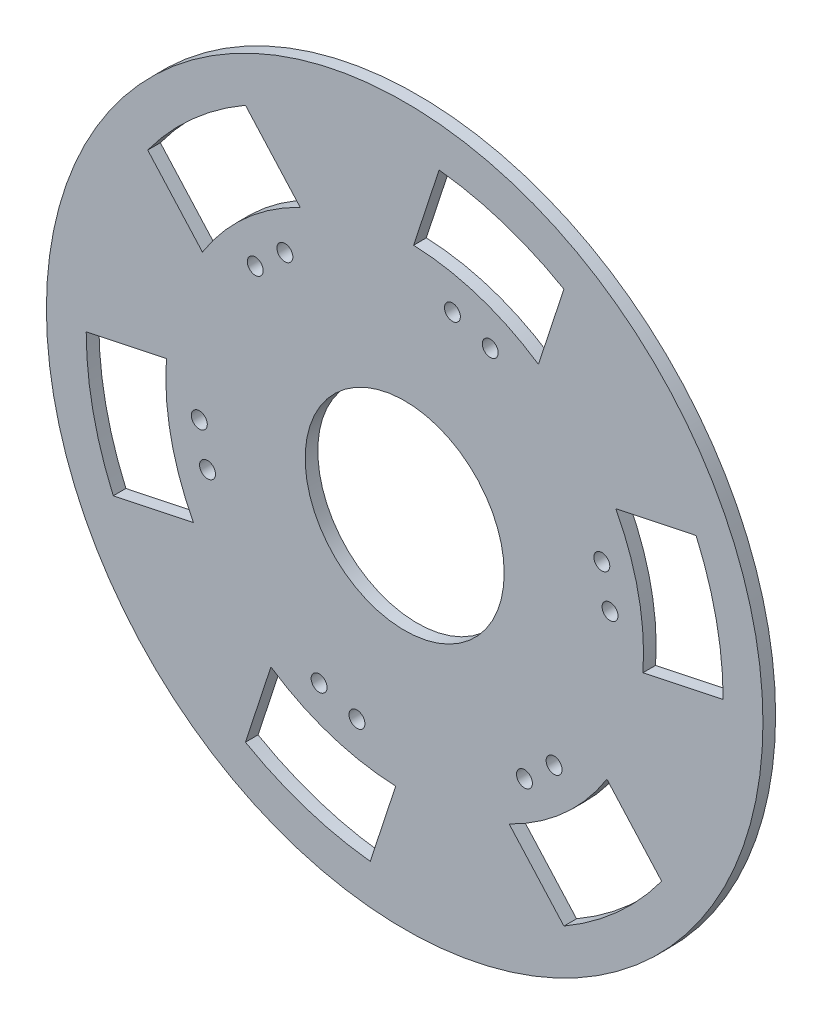
SolidWorks part; units mm, degrees
ref_plane "Front Plane" through (0, 0, 0) normal (0, 0, 1) x (1, 0, 0)
ref_plane "Top Plane" through (0, 0, 0) normal (0, 1, 0) x (1, 0, 0)
ref_plane "Right Plane" through (0, 0, 0) normal (1, 0, 0) x (0, 0, -1)
sketch "Sketch1" plane through (0, 0, 0) normal (0, 0, 1) x (1, 0, 0)
  circle A0 centre (0, 0) radius 90
  circle A1 centre (0, 0) radius 25
  dimension "D1" = 180
  dimension "D2" = 50
extrude "Boss-Extrude1" add sketch "Sketch1" along normal blind 3.175 contours A0 A1
sketch "Sketch2" plane through (0, 0, 0) normal (0, 0, -1) x (-1, 0, 0)
  circle A0 centre (-49.5233, 14.7488) radius 2
  circle A1 centre (-51.5847, 4.9636) radius 2
  circle A2 centre (-37.5345, -35.514) radius 2
  circle A3 centre (-30.091, -42.1919) radius 2
  circle A4 centre (11.9888, -50.2628) radius 2
  circle A5 centre (21.4938, -47.1555) radius 2
  circle A6 centre (49.5233, -14.7488) radius 2
  circle A7 centre (51.5847, -4.9636) radius 2
  circle A8 centre (37.5345, 35.514) radius 2
  circle A9 centre (30.091, 42.1919) radius 2
  circle A10 centre (-21.4938, 47.1555) radius 2
  circle A11 centre (-11.9888, 50.2628) radius 2
extrude "Cut-Extrude1" cut sketch "Sketch2" against normal through all
sketch "Sketch3" plane through (0, 0, 3.175) normal (0, 0, 1) x (1, 0, 0)
  line L0 (-49.5233, -14.7488) -> (-51.5847, -4.9636) construction
  line L1 (-21.4938, -47.1555) -> (-11.9888, -50.2628) construction
  line L2 (30.091, -42.1919) -> (37.5345, -35.514) construction
  line L3 (49.5233, 14.7488) -> (51.5847, 4.9636) construction
  line L4 (21.4938, 47.1555) -> (11.9888, 50.2628) construction
  line L5 (-30.091, 42.1919) -> (-37.5345, 35.514) construction
  line L6 (-88.0669, -18.553) -> (88.0669, 18.553) construction
  line L7 (-27.9661, -85.5447) -> (27.9661, 85.5447) construction
  line L8 (60.1009, -66.9917) -> (-60.1009, 66.9917) construction
  line L9 (-80, 0) -> (-62.1109, 3.7687)
  line L10 (-80, 0) -> (-73.2007, -32.2747)
  line L11 (-62.1109, 3.7687) -> (-55.3116, -28.506)
  line L12 (-73.2007, -32.2747) -> (-55.3116, -28.506)
  line L13 (-64.2562, -30.3904) -> (-71.0555, 1.8843) construction
  line L14 (-73.2007, -32.2747) -> (-53.0503, -28.0296)
  line L15 (-80, 0) -> (-59.8496, 4.2451)
  line L16 (-40, 69.282) -> (-27.7917, 55.674)
  line L17 (-40, 69.282) -> (-64.5511, 47.2563)
  line L18 (-64.5511, 47.2563) -> (-52.3428, 33.6483)
  line L19 (-27.7917, 55.674) -> (-52.3428, 33.6483)
  line L20 (-40, 69.282) -> (-26.2485, 53.9538)
  line L21 (-64.5511, 47.2563) -> (-50.7996, 31.9281)
  line L22 (40, 69.282) -> (34.3192, 51.9053)
  line L23 (40, 69.282) -> (8.6496, 79.531)
  line L24 (8.6496, 79.531) -> (2.9689, 62.1543)
  line L25 (34.3192, 51.9053) -> (2.9689, 62.1543)
  line L26 (40, 69.282) -> (33.6012, 49.7088)
  line L27 (8.6496, 79.531) -> (2.2508, 59.9578)
  line L28 (80, 0) -> (62.1109, -3.7687)
  line L29 (80, 0) -> (73.2007, 32.2747)
  line L30 (73.2007, 32.2747) -> (55.3116, 28.506)
  line L31 (62.1109, -3.7687) -> (55.3116, 28.506)
  line L32 (80, 0) -> (59.8496, -4.2451)
  line L33 (73.2007, 32.2747) -> (53.0503, 28.0296)
  line L34 (40, -69.282) -> (27.7917, -55.674)
  line L35 (40, -69.282) -> (64.5511, -47.2563)
  line L36 (64.5511, -47.2563) -> (52.3428, -33.6483)
  line L37 (27.7917, -55.674) -> (52.3428, -33.6483)
  line L38 (40, -69.282) -> (26.2485, -53.9538)
  line L39 (64.5511, -47.2563) -> (50.7996, -31.9281)
  line L40 (-40, -69.282) -> (-34.3192, -51.9053)
  line L41 (-40, -69.282) -> (-8.6496, -79.531)
  line L42 (-8.6496, -79.531) -> (-2.9689, -62.1543)
  line L43 (-34.3192, -51.9053) -> (-2.9689, -62.1543)
  line L44 (-40, -69.282) -> (-33.6012, -49.7088)
  line L45 (-8.6496, -79.531) -> (-2.2508, -59.9578)
  circle A0 centre (0, 0) radius 60
  circle A1 centre (0, 0) radius 80
  circle A2 centre (0, 0) radius 90 construction
  point P19 (0, 0)
  point P38 (0, 0)
  point P45 (0, 0)
  point P46 (-67.6558, -14.253)
  point P81 (0, 0)
  dimension "D1" = 120
  dimension "D2" = 160
  dimension "D3" = 6
extrude "Cut-Extrude2" cut sketch "Sketch3" against normal through all contours L10 L12 L11 L9 | L10 A1 | A0 L15 L11 | A0 L11 L14 | L43 L40 L41 L42 | A0 L44 L43 | A0 L43 L45 | L41 A1 | L37 L34 L35 L36 | A0 L38 L37 | A0 L37 L39 | L35 A1 | L31 L28 L29 L30 | A0 L31 L33 | A0 L32 L31 | L29 A1 | L19 L16 L17 L18 | L25 L22 L23 L24 | A0 L25 L27 | A0 L26 L25 | L23 A1 | L17 A1 | A0 L19 L21 | A0 L20 L19
